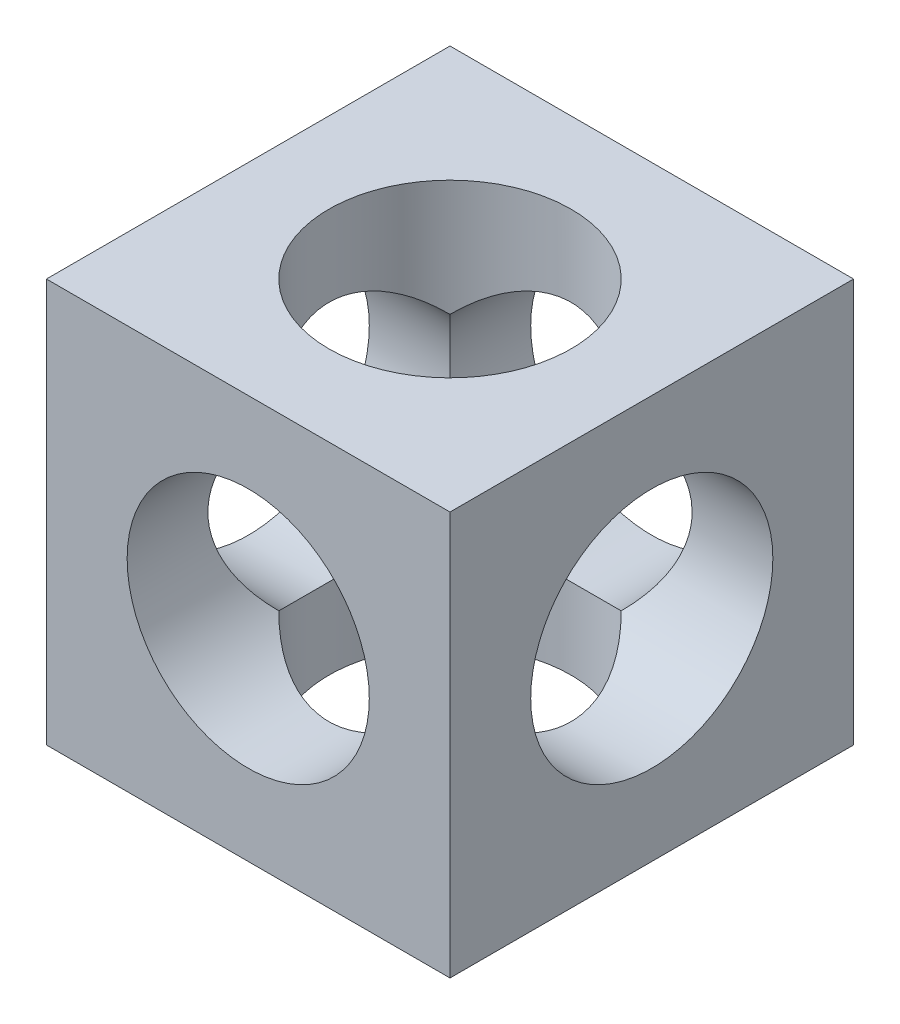
SolidWorks part; units mm, degrees
ref_plane "前视基准面" through (0, 0, 0) normal (0, 0, 1) x (1, 0, 0)
ref_plane "上视基准面" through (0, 0, 0) normal (0, 1, 0) x (1, 0, 0)
ref_plane "右视基准面" through (0, 0, 0) normal (1, 0, 0) x (0, 0, -1)
other "Configuration Table"
sketch "草图1" plane through (0, 0, 0) normal (0, 1, 0) x (1, 0, 0)
  line L0 (2.5, 0) -> (2.5, 5) construction
  line L1 (0, 0) -> (5, 0)
  line L2 (0, 0) -> (0, 5)
  line L3 (0, 5) -> (5, 5)
  line L4 (5, 0) -> (5, 5)
  line L6 (0, 2.5) -> (5, 2.5) construction
  circle A0 centre (2.5, 2.5) radius 1.5
  dimension "D3" = 3
  dimension "D1" = 5
  dimension "D2" = 5
extrude "凸台-拉伸1" add sketch "草图1" along normal blind 5
sketch "草图2" plane through (0, 0, 0) normal (0, 0, 1) x (1, 0, 0)
  line L0 (2.5, 0) -> (2.5, 5) construction
  line L1 (0, 0) -> (5, 0) construction
  line L2 (0, 5) -> (5, 5) construction
  line L3 (0, 2.5) -> (5, 2.5) construction
  line L4 (0, 5) -> (0, 0) construction
  line L5 (5, 5) -> (5, 0) construction
  circle A0 centre (2.5, 2.5) radius 1.5
  dimension "D1" = 3
extrude "切除-拉伸1" cut sketch "草图2" against normal blind 5 contours A0
sketch "草图3" plane through (5, 0, 0) normal (1, 0, 0) x (0, 0, -1)
  line L0 (2.5, 0) -> (2.5, 5) construction
  line L1 (0, 0) -> (5, 0) construction
  line L2 (0, 5) -> (5, 5) construction
  line L4 (0, 5) -> (0, 0) construction
  line L5 (0, 2.5) -> (5, 2.5) construction
  line L6 (5, 5) -> (5, 0) construction
  circle A0 centre (2.5, 2.5) radius 1.5
  dimension "D1" = 3
extrude "切除-拉伸2" cut sketch "草图3" against normal blind 5 contours A0
